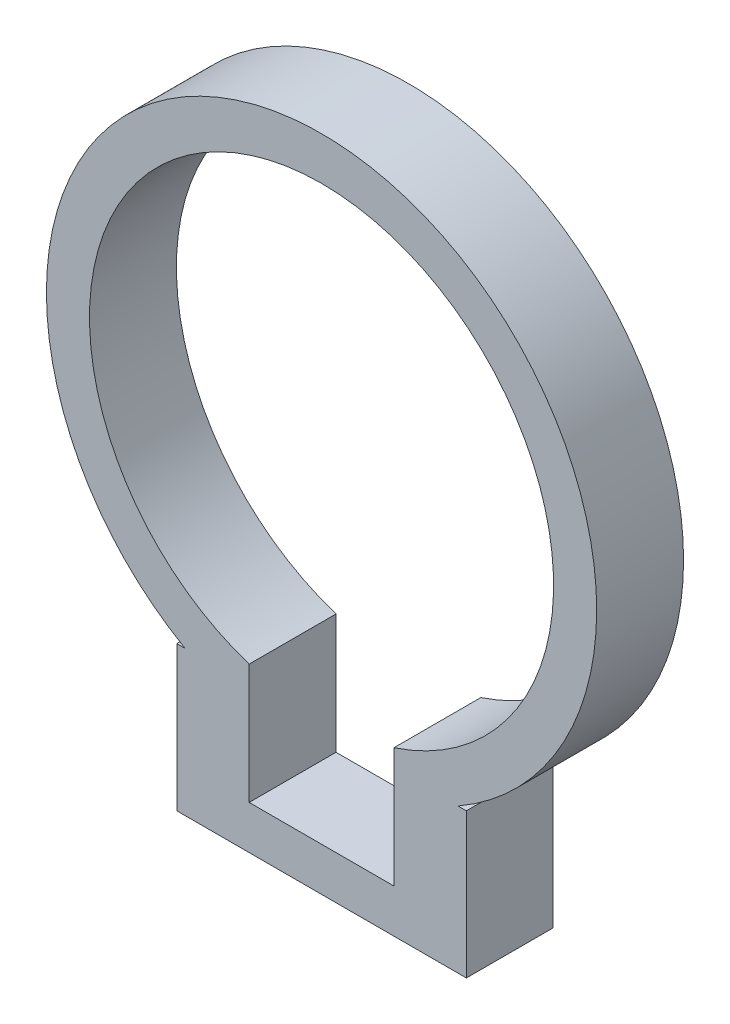
SolidWorks part; units mm, degrees
ref_plane "Plan de face" through (0, 0, 0) normal (0, 0, 1) x (1, 0, 0)
ref_plane "Plan de dessus" through (0, 0, 0) normal (0, 1, 0) x (1, 0, 0)
ref_plane "Plan de droite" through (0, 0, 0) normal (1, 0, 0) x (0, 0, -1)
sketch "Esquisse1" plane through (0, 0, 0) normal (0, 0, 1) x (1, 0, 0)
  line L1 (10, -5) -> (-10, -5)
  line L2 (10, -5) -> (10, 5)
  line L3 (10, 5) -> (-10, 5)
  line L4 (-10, -5) -> (-10, 5)
  line L5 (10, -5) -> (-10, 5) construction
  line L6 (10, 5) -> (-10, -5) construction
  point P0 (0, 0)
extrude "Boss.-Extru.1" add sketch "Esquisse1" along normal blind 6
sketch "Esquisse2" plane through (0, 0, 6) normal (0, 0, 1) x (1, 0, 0)
  circle A0 centre (0, 21.4974) radius 19
extrude "Boss.-Extru.2" add sketch "Esquisse2" against normal blind 6
sketch "Esquisse3" plane through (0, 0, 6) normal (0, 0, 1) x (1, 0, 0)
  circle A0 centre (0, 21.4974) radius 16.025
extrude "Enlèv. mat.-Extru.1" cut sketch "Esquisse3" against normal blind 6
sketch "Esquisse4" plane through (0, 0, 6) normal (0, 0, 1) x (1, 0, 0)
  line L0 (-10, -5) -> (10, -5) construction
  line L1 (-5, 6.2724) -> (5, 6.2724)
  line L2 (-5, 6.2724) -> (-5, -2)
  line L3 (-5, -2) -> (5, -2)
  line L4 (5, 6.2724) -> (5, -2)
  line L5 (-10, 5) -> (-10, -5) construction
  line L6 (10, -5) -> (10, 5) construction
  circle A0 centre (0, 21.4974) radius 16.025 construction
  dimension "D1" = 3
  dimension "D2" = 5
  dimension "D3" = 5
extrude "Enlèv. mat.-Extru.2" cut sketch "Esquisse4" against normal blind 10
